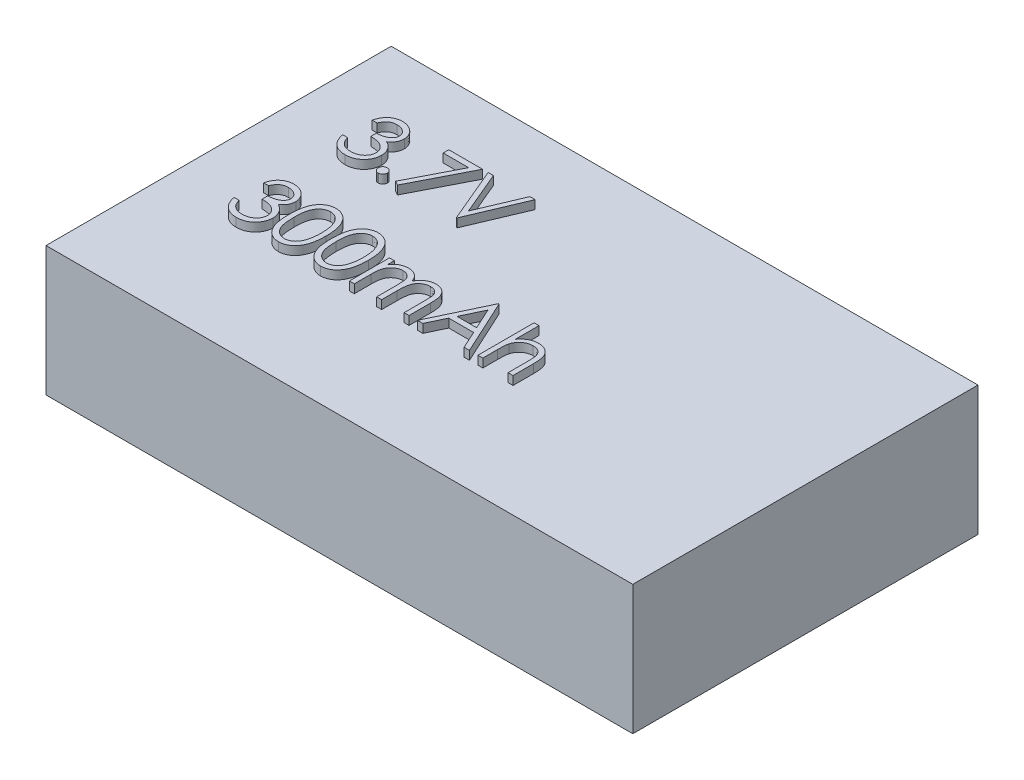
SolidWorks part; units mm, degrees
ref_plane "Front Plane" through (0, 0, 0) normal (0, 0, 1) x (1, 0, 0)
ref_plane "Top Plane" through (0, 0, 0) normal (0, 1, 0) x (1, 0, 0)
ref_plane "Right Plane" through (0, 0, 0) normal (1, 0, 0) x (0, 0, -1)
sketch "Sketch1" plane through (0, 0, 0) normal (0, 1, 0) x (1, 0, 0)
  line L1 (17, -10) -> (-17, -10)
  line L2 (17, -10) -> (17, 10)
  line L3 (17, 10) -> (-17, 10)
  line L4 (-17, -10) -> (-17, 10)
  line L5 (17, -10) -> (-17, 10) construction
  line L6 (17, 10) -> (-17, -10) construction
  point P0 (0, 0)
  dimension "D1" = 34
  dimension "D2" = 20
extrude "Boss-Extrude1" add sketch "Sketch1" along normal blind 7.5
sketch "Sketch2" plane through (0, 7.5, 0) normal (0, 1, 0) x (1, 0, 0)
  text T0 "3.7V \r\n300mAh"
extrude "Boss-Extrude2" add sketch "Sketch2" along normal blind 0.5
